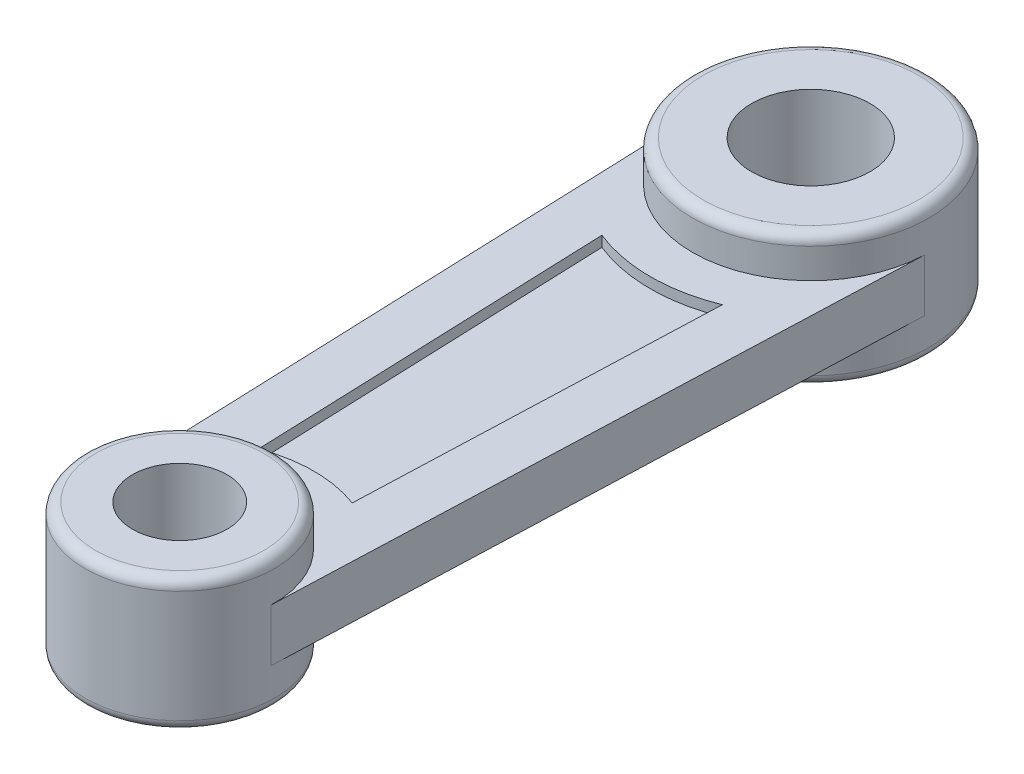
SolidWorks part; units mm, degrees
ref_plane "Front Plane" through (0, 0, 0) normal (0, 0, 1) x (1, 0, 0)
ref_plane "Top Plane" through (0, 0, 0) normal (0, 1, 0) x (1, 0, 0)
ref_plane "Right Plane" through (0, 0, 0) normal (1, 0, 0) x (0, 0, -1)
sketch "Sketch1" plane through (0, 0, 0) normal (0, 1, 0) x (1, 0, 0)
  circle A0 centre (0, 0) radius 45
  circle A1 centre (0, 0) radius 22.5
  circle A2 centre (0, 300) radius 56.25
  circle A3 centre (0, 300) radius 28.15
  point P7 (0, 0)
  dimension "D1" = 112.5
  dimension "D2" = 56.3
  dimension "D3" = 90
  dimension "D4" = 45
  dimension "D5" = 300
extrude "Boss-Extrude1" add sketch "Sketch1" along normal mid plane 63.3
sketch "Sketch2" plane through (0, 0, 0) normal (0, 1, 0) x (1, 0, 0)
  line L0 (-56.2104, 297.8906) -> (-44.9683, -1.6875)
  line L1 (56.2104, 297.8906) -> (44.9683, -1.6875)
  circle A0 centre (0, 0) radius 45 construction
  circle A1 centre (0, 300) radius 56.25 construction
  arc A2 (44.9683, -1.6875) -> (-44.9683, -1.6875) centre (0, 0) ccw
  arc A3 (-56.2104, 297.8906) -> (56.2104, 297.8906) centre (0, 300) ccw
extrude "Boss-Extrude2" add sketch "Sketch2" along normal mid plane 25
sketch "Sketch3" plane through (0, 12.5, 0) normal (0, 1, 0) x (1, 0, 0)
  line L2 (-31.228, 298.8281) -> (-19.9859, -0.75)
  line L3 (-28.6198, 229.3249) -> (-22.2559, 59.7389)
  line L5 (19.9859, -0.75) -> (31.228, 298.8281)
  line L6 (22.2559, 59.7389) -> (28.6198, 229.3249)
  arc A0 (-28.6198, 229.3249) -> (28.6198, 229.3249) centre (0, 300) ccw
  arc A1 (22.2559, 59.7389) -> (-22.2559, 59.7389) centre (0, 0) ccw
  dimension "D1" = 152.5
  dimension "D2" = 127.5
  dimension "D3" = 25
  dimension "D4" = 25
extrude "Cut-Extrude1" cut sketch "Sketch3" against normal blind 5
sketch "Sketch4" plane through (0, -12.5, 0) normal (0, -1, 0) x (1, 0, 0)
  line L0 (22.2559, -59.7389) -> (28.6198, -229.3249) construction
  line L1 (-28.6198, -229.3249) -> (-22.2559, -59.7389) construction
  line L2 (22.2559, -59.7389) -> (28.6198, -229.3249)
  line L3 (-28.6198, -229.3249) -> (-22.2559, -59.7389)
  arc A0 (28.6198, -229.3249) -> (-28.6198, -229.3249) centre (0, -300) ccw construction
  arc A1 (-22.2559, -59.7389) -> (22.2559, -59.7389) centre (0, 0) ccw construction
  arc A2 (28.6198, -229.3249) -> (-28.6198, -229.3249) centre (0, -300) ccw
  arc A3 (-22.2559, -59.7389) -> (22.2559, -59.7389) centre (0, 0) ccw
extrude "Cut-Extrude2" cut sketch "Sketch4" against normal blind 5
fillet "Fillet1" radius 5 4 edges at (0, -31.65, -243.75) (0, 31.65, -243.75) (0, -31.65, 45) (0, 31.65, 45)
